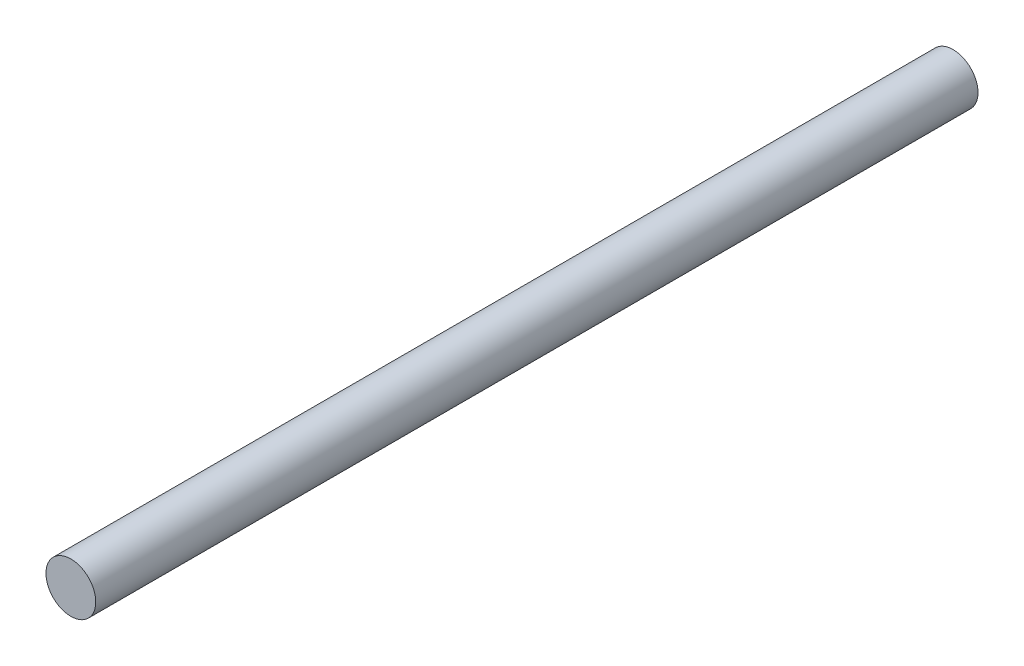
SolidWorks part; units mm, degrees
ref_plane "Plano frontal" through (0, 0, 0) normal (0, 0, 1) x (1, 0, 0)
ref_plane "Plano superior" through (0, 0, 0) normal (0, 1, 0) x (1, 0, 0)
ref_plane "Plano direito" through (0, 0, 0) normal (1, 0, 0) x (0, 0, -1)
sketch "Esboço1" plane through (0, 0, 0) normal (0, 0, 1) x (1, 0, 0)
  circle A0 centre (0, 0) radius 1.75
  dimension "D1" = 3.5
extrude "Ressalto-extrusão1" add sketch "Esboço1" along normal blind 62
